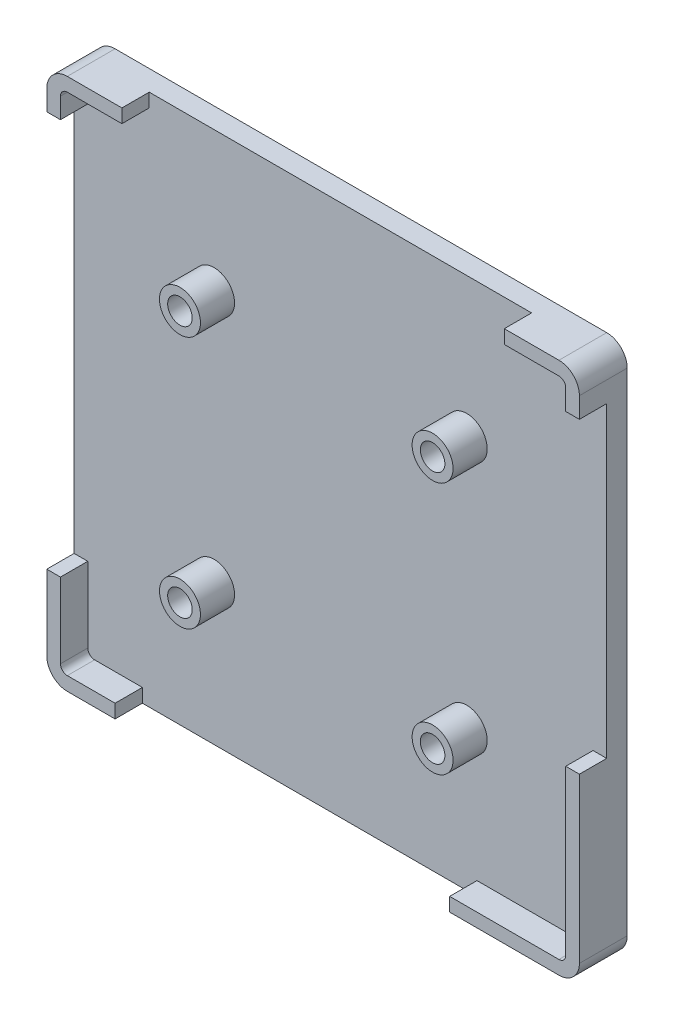
SolidWorks part; units mm, degrees
ref_plane "前视基准面" through (0, 0, 0) normal (0, 0, 1) x (1, 0, 0)
ref_plane "上视基准面" through (0, 0, 0) normal (0, 1, 0) x (1, 0, 0)
ref_plane "右视基准面" through (0, 0, 0) normal (1, 0, 0) x (0, 0, -1)
sketch "草图1" plane through (0, 0, 0) normal (0, 0, 1) x (1, 0, 0)
  line L0 (-36, -39) -> (36, -39)
  line L1 (39, -36) -> (39, 36)
  line L2 (36, 39) -> (-36, 39)
  line L3 (-39, 36) -> (-39, -36)
  arc A0 (36, -39) -> (39, -36) centre (36, -36) ccw
  arc A1 (39, 36) -> (36, 39) centre (36, 36) ccw
  arc A2 (-36, 39) -> (-39, 36) centre (-36, 36) ccw
  arc A3 (-39, -36) -> (-36, -39) centre (-36, -36) ccw
  dimension "D1" = 3
  dimension "D2" = 39
  dimension "D3" = 39
  dimension "D4" = 39
extrude "底托基础_总边高7" add sketch "草图1" along normal blind 7
sketch "草图2" plane through (0, 0, 0) normal (0, 0, 1) x (1, 0, 0)
  line L0 (-36, -37) -> (36, -37)
  line L1 (37, -36) -> (37, 36)
  line L2 (36, 37) -> (-36, 37)
  line L3 (-37, 36) -> (-37, -36)
  arc A0 (36, -37) -> (37, -36) centre (36, -36) ccw
  arc A1 (37, 36) -> (36, 37) centre (36, 36) ccw
  arc A2 (-36, 37) -> (-37, 36) centre (-36, 36) ccw
  arc A3 (-37, -36) -> (-36, -37) centre (-36, -36) ccw
  dimension "D1" = 1
  dimension "D2" = 37
  dimension "D3" = 37
  dimension "D4" = 37
extrude "底腔_实体绝缘底厚3_侧壁2" cut sketch "草图2" along normal blind 4 from offset 3
sketch "草图3" plane through (0, 0, 0) normal (0, 0, 1) x (1, 0, 0)
  line L1 (-42, -25) -> (-36, -25)
  line L2 (-42, -25) -> (-42, 33)
  line L3 (-42, 33) -> (-36, 33)
  line L4 (-36, -25) -> (-36, 33)
  line L5 (-42, -25) -> (-36, 33) construction
  line L6 (-42, 33) -> (-36, -25) construction
  dimension "D1" = 36
  dimension "D2" = 42
  dimension "D3" = 33
  dimension "D4" = 25
extrude "左侧M3_M4编码器及5V接口开口_不切穿绝缘底板" cut sketch "草图3" along normal blind 4 from offset 3
sketch "草图4" plane through (0, 0, 0) normal (0, 0, 1) x (1, 0, 0)
  line L1 (36, -12) -> (42, -12)
  line L2 (36, -12) -> (36, 33)
  line L3 (36, 33) -> (42, 33)
  line L4 (42, -12) -> (42, 33)
  line L5 (36, -12) -> (42, 33) construction
  line L6 (36, 33) -> (42, -12) construction
  dimension "D1" = 36
  dimension "D2" = 42
  dimension "D3" = 33
  dimension "D4" = 12
extrude "右侧M2_M1及电机接口开口_不切穿绝缘底板" cut sketch "草图4" along normal blind 4 from offset 3
sketch "草图5" plane through (0, 0, 0) normal (0, 0, 1) x (1, 0, 0)
  line L1 (-28, 36) -> (28, 36)
  line L2 (-28, 36) -> (-28, 42)
  line L3 (-28, 42) -> (28, 42)
  line L4 (28, 36) -> (28, 42)
  line L5 (-28, 36) -> (28, 42) construction
  line L6 (-28, 42) -> (28, 36) construction
  dimension "D1" = 28
  dimension "D2" = 28
  dimension "D3" = 36
  dimension "D4" = 42
extrude "上侧控制与编码器及M3接口开口_不切穿绝缘底板" cut sketch "草图5" along normal blind 4 from offset 3
sketch "草图6" plane through (0, 0, 0) normal (0, 0, 1) x (1, 0, 0)
  line L1 (-29, -42) -> (20, -42)
  line L2 (-29, -42) -> (-29, -36)
  line L3 (-29, -36) -> (20, -36)
  line L4 (20, -42) -> (20, -36)
  line L5 (-29, -42) -> (20, -36) construction
  line L6 (-29, -36) -> (20, -42) construction
  dimension "D1" = 20
  dimension "D2" = 29
  dimension "D3" = 36
  dimension "D4" = 42
extrude "下侧凤凰端子_DC_电源开关共用开口_不切穿绝缘底板" cut sketch "草图6" along normal blind 4 from offset 3
sketch "草图7" plane through (0, 0, 0) normal (0, 0, 1) x (1, 0, 0)
  circle A0 centre (-18.5, -18.5) radius 3
  circle A1 centre (-18.5, 18.5) radius 3
  circle A2 centre (18.5, -18.5) radius 3
  circle A3 centre (18.5, 18.5) radius 3
  dimension "D1" = 6
  dimension "D2" = 18.5
  dimension "D3" = 18.5
  dimension "D4" = 18.5
  dimension "D5" = 18.5
extrude "四根绝缘支柱_板背净距5" add sketch "草图7" along normal blind 5 from offset 3
sketch "草图8" plane through (0, 0, 0) normal (0, 0, 1) x (1, 0, 0)
  circle A0 centre (-18.5, -18.5) radius 1.8
  circle A1 centre (-18.5, 18.5) radius 1.8
  circle A2 centre (18.5, -18.5) radius 1.8
  circle A3 centre (18.5, 18.5) radius 1.8
  dimension "D1" = 3.6
  dimension "D2" = 18.5
  dimension "D3" = 18.5
  dimension "D4" = 18.5
  dimension "D5" = 18.5
extrude "PCB与底部对齐通孔_单边0.3" cut sketch "草图8" along normal blind 8
